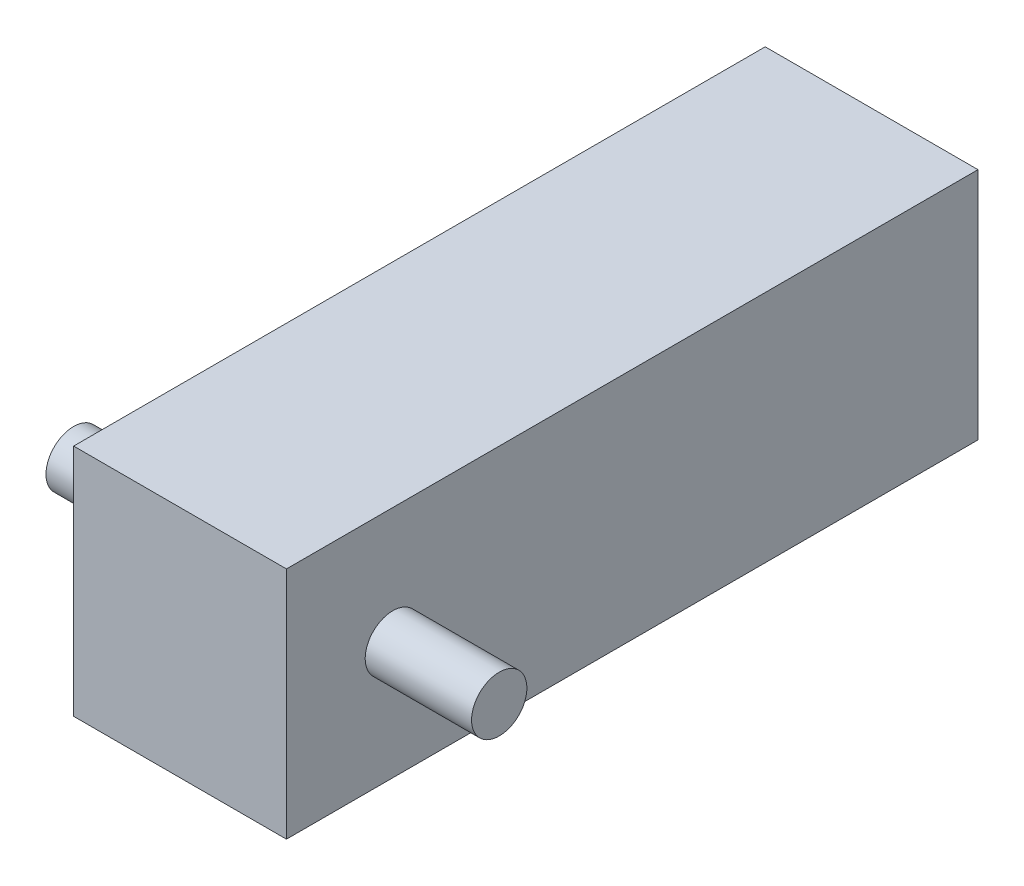
SolidWorks part; units mm, degrees
ref_plane "Alzado" through (0, 0, 0) normal (0, 0, 1) x (1, 0, 0)
ref_plane "Planta" through (0, 0, 0) normal (0, 1, 0) x (1, 0, 0)
ref_plane "Vista lateral" through (0, 0, 0) normal (1, 0, 0) x (0, 0, -1)
sketch "Croquis1" plane through (0, 0, 0) normal (0, 1, 0) x (1, 0, 0)
  line L1 (-10, -32.5) -> (10, -32.5)
  line L2 (-10, -32.5) -> (-10, 32.5)
  line L3 (-10, 32.5) -> (10, 32.5)
  line L4 (10, -32.5) -> (10, 32.5)
  line L5 (-10, -32.5) -> (10, 32.5) construction
  line L6 (-10, 32.5) -> (10, -32.5) construction
  point P0 (0, 0)
  dimension "D1" = 20
  dimension "D2" = 65
extrude "Saliente-Extruir1" add sketch "Croquis1" along normal mid plane 22
sketch "Croquis3" plane through (0, 0, 0) normal (-1, 0, 0) x (0, 0, 1)
  line L0 (-45.6395, 0) -> (43.5074, 0) construction
  line L1 (32.5, 11) -> (32.5, -11) construction
  circle A0 centre (22.5, 0) radius 2.6
  dimension "D1" = 5.2
  dimension "D2" = 10
extrude "Saliente-Extruir2" add sketch "Croquis3" along normal mid plane 40
